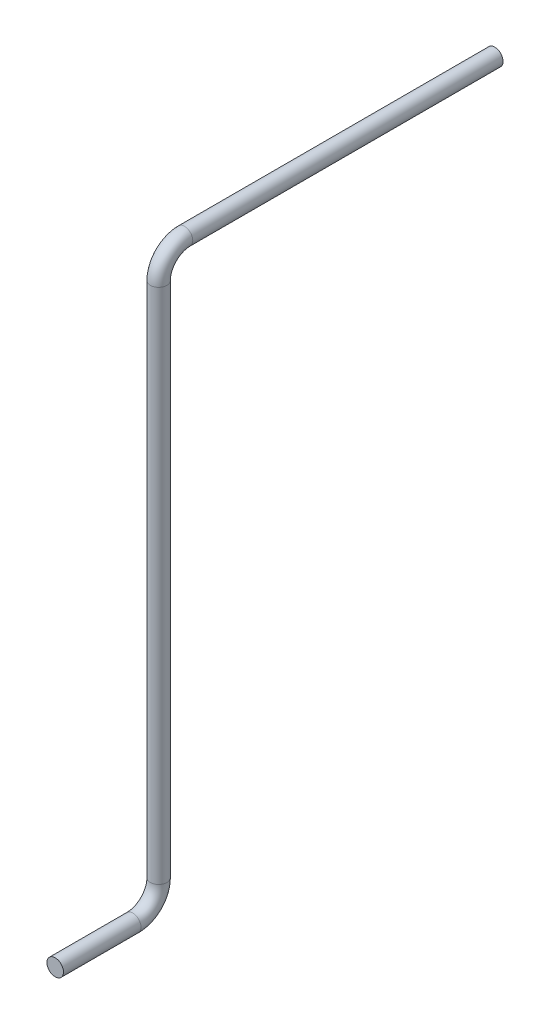
SolidWorks part; units mm, degrees
material "AISI 1020 Steel, Cold Rolled"
ref_plane "Front Plane" through (0, 0, 0) normal (0, 0, 1) x (1, 0, 0)
ref_plane "Top Plane" through (0, 0, 0) normal (0, 1, 0) x (1, 0, 0)
ref_plane "Right Plane" through (0, 0, 0) normal (1, 0, 0) x (0, 0, -1)
sketch "Sketch1" plane through (0, 0, 0) normal (0, 0, 1) x (1, 0, 0)
  circle A0 centre (0, 0) radius 1.6
  dimension "D1" = 3.2
sketch "Sketch2" plane through (0, 0, 0) normal (1, 0, 0) x (0, 0, -1)
  line L0 (0, 0) -> (15, 0)
  line L1 (20, 5) -> (20, 105)
  line L2 (25, 110) -> (85, 110)
  arc A0 (15, 0) -> (20, 5) centre (15, 5) ccw
  arc A1 (20, 105) -> (25, 110) centre (25, 105) cw
  dimension "D4" = 5
  dimension "D5" = 5
  dimension "D1" = 20
  dimension "D2" = 110
  dimension "D3" = 60
sweep "Sweep1" add profiles "Sketch1" path "Sketch2"
